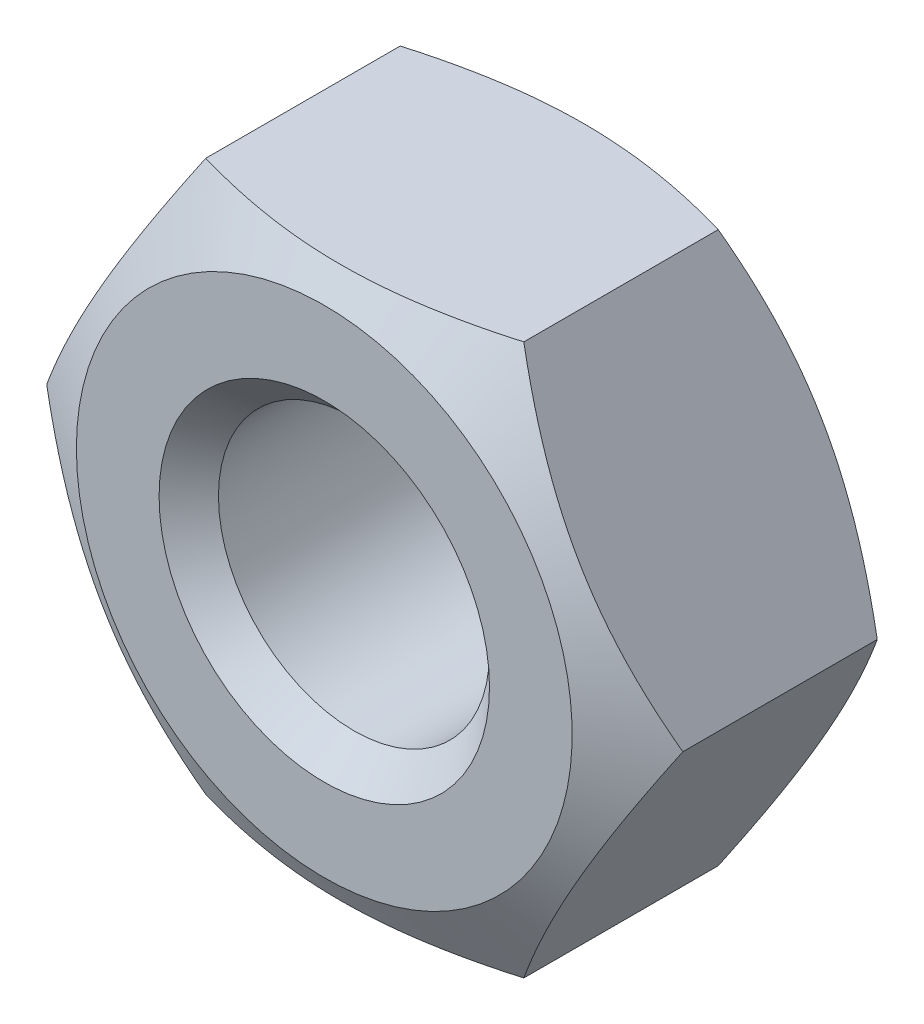
SolidWorks part; units mm, degrees
ref_plane "СПЕРЕДИ" through (0, 0, 0) normal (0, 0, 1) x (1, 0, 0)
ref_plane "ПЛ_ВЫРАВ" through (0, 0, 0) normal (0, 1, 0) x (1, 0, 0)
ref_plane "СПРАВА" through (0, 0, 0) normal (1, 0, 0) x (0, 0, -1)
sketch "Эскиз2" plane through (0, 0, 0) normal (0, 0, 1) x (1, 0, 0)
  line L0 (-20, 0) -> (20, 0) construction
  line L1 (5.7735, 0) -> (2.8868, 5)
  line L2 (2.8868, 5) -> (-2.8868, 5)
  line L3 (-2.8868, 5) -> (-5.7735, 0)
  line L4 (-5.7735, 0) -> (-2.8868, -5)
  line L5 (-2.8868, -5) -> (2.8868, -5)
  line L6 (2.8868, -5) -> (5.7735, 0)
  circle A0 centre (0, 0) radius 5 construction
  dimension "S" = 10
extrude "Основание-Вытянуть" add sketch "Эскиз2" along normal blind 5
sketch "Эскиз3" plane through (0, 0, 0) normal (0, 1, 0) x (1, 0, 0)
  line L0 (-5.7735, 0) -> (-4.5, 0)
  line L1 (-2.8868, 0) -> (-5.7735, 0) construction
  line L2 (-5.7735, 0) -> (-5.7735, -0.7353)
  line L3 (-5.7735, -5) -> (-5.7735, 0) construction
  line L4 (-5.7735, -0.7353) -> (-4.5, 0)
  line L6 (-4.5, 10) -> (-4.5, -20) construction
  line L7 (-5.7735, -5) -> (-5.7735, -4.2647)
  line L8 (0, 10) -> (0, -20) construction
  line L9 (-5.7735, -4.2647) -> (-4.5, -5)
  line L10 (-2.8868, -5) -> (-5.7735, -5) construction
  line L11 (-5.7735, -5) -> (-4.5, -5)
  dimension "D1" = 30
  dimension "D4" = 30
  dimension "Dw" = 9
revolve "Вырез-Повернуть1" cut sketch "Эскиз3" angle 360 about L8
hole_wizard "Отверстие резьбовое" positions "Эскиз5" profile "Эскиз4" tap size "M16x2.0" standard "Ansi Метрический" end condition up to next
sketch "Эскиз5" plane through (0, 0, 0) normal (0, 0, -1) x (-1, 0, 0)
  point P0 (0, 0)
sketch "Эскиз4" plane through (0, 0, 0) normal (1, 0, 0) x (0, 1, 0)
  line L0 (0, 0) -> (0, 5)
  line L1 (0, 5) -> (3, 5)
  line L2 (2.46, 4.46) -> (2.46, 0.54)
  line L3 (2.46, 0.54) -> (3, 0)
  line L5 (3, 0) -> (0, 0)
  line L6 (-2.46, 0.54) -> (-3, 0) construction
  line L7 (3, 5) -> (2.46, 4.46)
  line L8 (-3, 5) -> (-2.46, 4.46) construction
  line L11 (0, -6.35) -> (0, 107.95) construction
  dimension "Диаметр сквозного отверстия" = 4.92
  dimension "Глубина сквозного отверстия" = 5
  dimension "DZ" = 6
  dimension "UGz" = 90
cosmetic thread "Условное изображение резьбы1" parameters "D"=6
